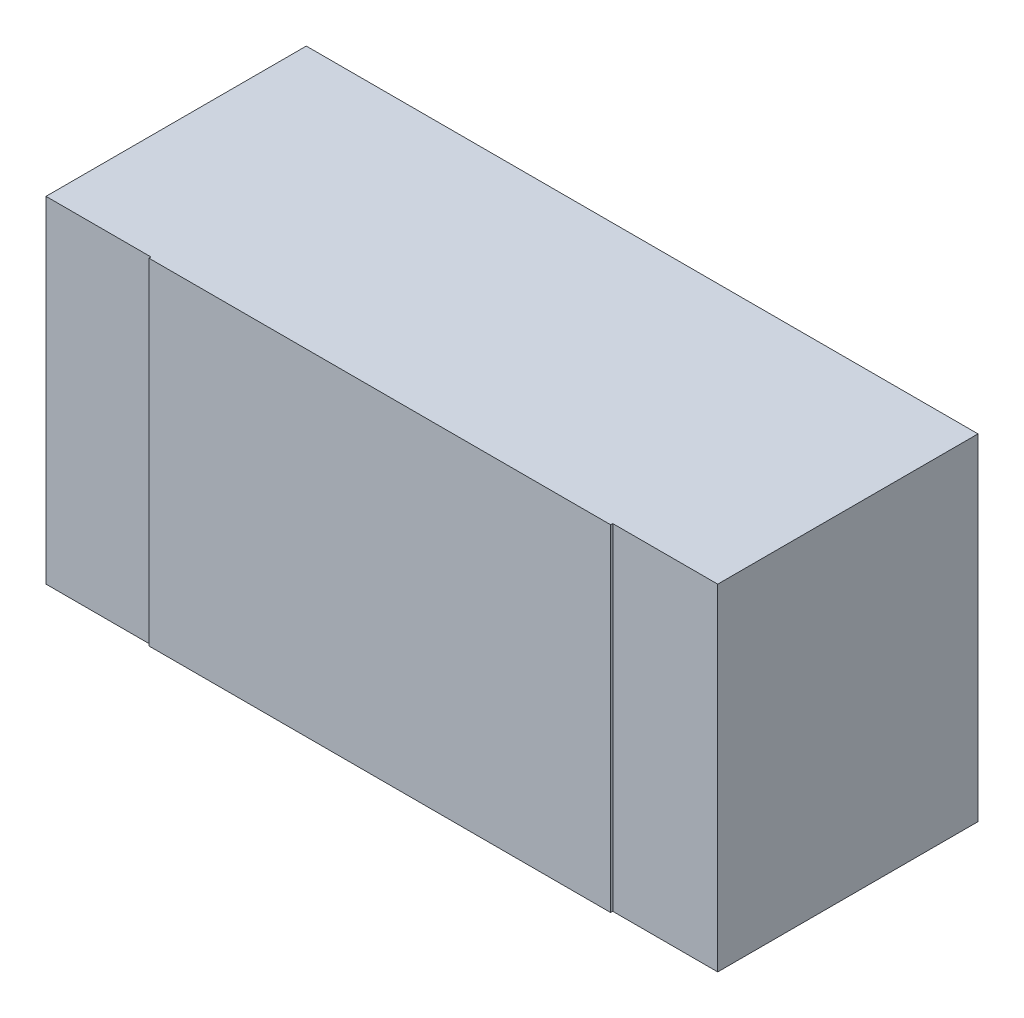
SolidWorks part; units mm, degrees
ref_plane "Спереди" through (0, 0, 0) normal (0, 0, 1) x (1, 0, 0)
ref_plane "Сверху" through (0, 0, 0) normal (0, 1, 0) x (1, 0, 0)
ref_plane "Справа" through (0, 0, 0) normal (1, 0, 0) x (0, 0, -1)
sketch "Эскиз2" plane through (0, 0, 0) normal (0, 0, 1) x (1, 0, 0)
  line L0 (-0.3, 0) -> (2.9, 0) construction
  line L1 (-0.3, 0.8) -> (2.9, 0.8)
  line L2 (-0.3, 0.8) -> (-0.3, -0.8)
  line L3 (-0.3, -0.8) -> (2.9, -0.8)
  line L4 (2.9, 0.8) -> (2.9, -0.8)
  line L5 (1.3, 0.8) -> (1.3, -0.8) construction
  dimension "D1" = 3.2
  dimension "D2" = 1.6
  dimension "D3" = 1.3
extrude "Вытянуть1" add sketch "Эскиз2" along normal blind 1.25
sketch "Эскиз3" plane through (0, 0, 1.25) normal (0, 0, 1) x (1, 0, 0)
  line L0 (2.9, 0.8) -> (-0.3, 0.8) construction
  line L1 (-0.3, 0.8) -> (0.2, 0.8)
  line L2 (-0.3, 0.8) -> (-0.3, -0.8)
  line L3 (-0.3, -0.8) -> (0.2, -0.8)
  line L4 (0.2, 0.8) -> (0.2, -0.8)
  line L5 (2.4, 0.8) -> (2.9, 0.8)
  line L6 (2.4, 0.8) -> (2.4, -0.8)
  line L7 (2.4, -0.8) -> (2.9, -0.8)
  line L8 (2.9, 0.8) -> (2.9, -0.8)
  line L9 (-0.3, -0.8) -> (2.9, -0.8) construction
  dimension "D1" = 0.5
  dimension "D2" = 0.5
extrude "Вырез-Вытянуть1" cut sketch "Эскиз3" against normal blind 0.01
